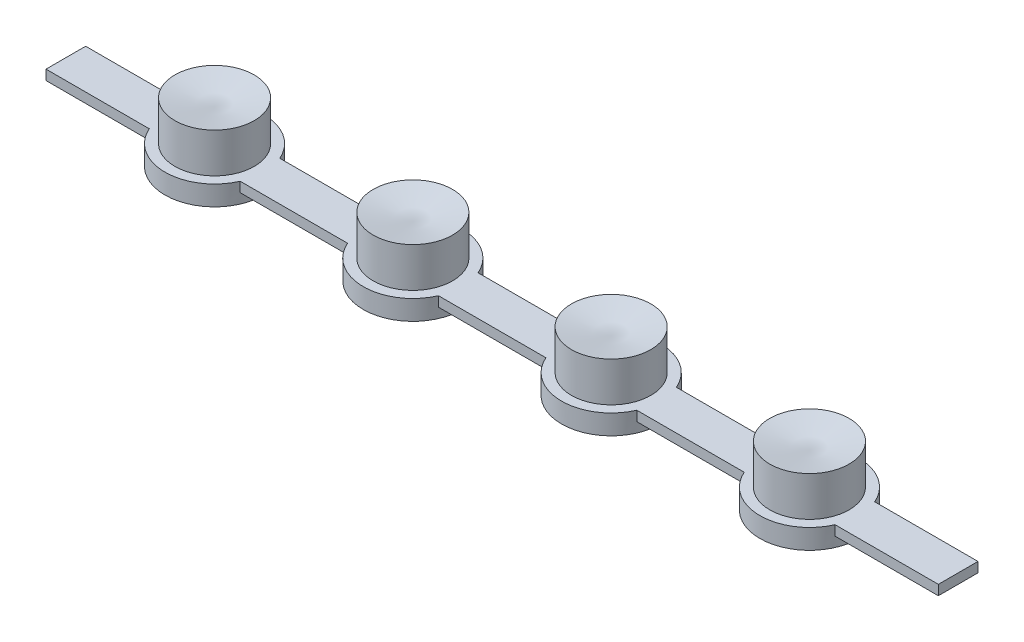
SolidWorks part; units mm, degrees
ref_plane "Front Plane" through (0, 0, 0) normal (0, 0, 1) x (1, 0, 0)
ref_plane "Top Plane" through (0, 0, 0) normal (0, 1, 0) x (1, 0, 0)
ref_plane "Right Plane" through (0, 0, 0) normal (1, 0, 0) x (0, 0, -1)
sketch "Sketch1" plane through (0, 0, 0) normal (0, 1, 0) x (1, 0, 0)
  circle A0 centre (0, 0) radius 2
  dimension "D1" = 4
extrude "Boss-Extrude1" add sketch "Sketch1" along normal blind 3
sketch "Sketch2" plane through (0, 0, 0) normal (1, 0, 0) x (0, 0, -1)
  line L0 (0, 3) -> (0, 2.6)
  line L1 (2, 3) -> (-2, 3) construction
  line L2 (0, 2.6) -> (-2, 3)
  line L3 (-2, 3) -> (0, 3)
  dimension "D1" = 0.4
revolve "Cut-Revolve1" cut sketch "Sketch2" angle 360 about L0
sketch "Sketch3" plane through (0, 0, 0) normal (0, 1, 0) x (1, 0, 0)
  line L0 (0, 0) -> (-5.2939, 0) construction
  line L2 (33, -2.5) -> (-7, -2.5) construction
  line L3 (33, -2.5) -> (33, 2.5) construction
  line L4 (33, 2.5) -> (-7, 2.5) construction
  line L5 (-7, -2.5) -> (-7, 2.5) construction
  line L6 (33, -2.5) -> (-7, 2.5) construction
  line L7 (33, 2.5) -> (-7, -2.5) construction
  circle A4 centre (0, 0) radius 2 construction
  circle A5 centre (0, 0) radius 2.5
  point P1 (13, 0)
  dimension "D4" = 5
  dimension "D1" = 5
  dimension "D2" = 40
  dimension "D3" = 5
extrude "Boss-Extrude3" add sketch "Sketch3" along normal blind 1
pattern_linear "LPattern4" count 4 spacing 10 along (1, 0, 0) of bodies 104
sketch "Sketch4" plane through (0, 1, 0) normal (0, 1, 0) x (1, 0, 0)
  line L0 (0, 0) -> (16.4971, 0) construction
  line L2 (-7.5, -1) -> (37.5, -1)
  line L3 (-7.5, -1) -> (-7.5, 1)
  line L4 (-7.5, 1) -> (37.5, 1)
  line L5 (37.5, -1) -> (37.5, 1)
  line L6 (-7.5, -1) -> (37.5, 1) construction
  line L7 (-7.5, 1) -> (37.5, -1) construction
  circle A1 centre (0, 0) radius 2.5 construction
  circle A4 centre (30, 0) radius 2.5 construction
  point P1 (15, 0)
  dimension "D1" = 2
  dimension "D2" = 5
  dimension "D3" = 5
extrude "Boss-Extrude4" add sketch "Sketch4" against normal blind 0.5
